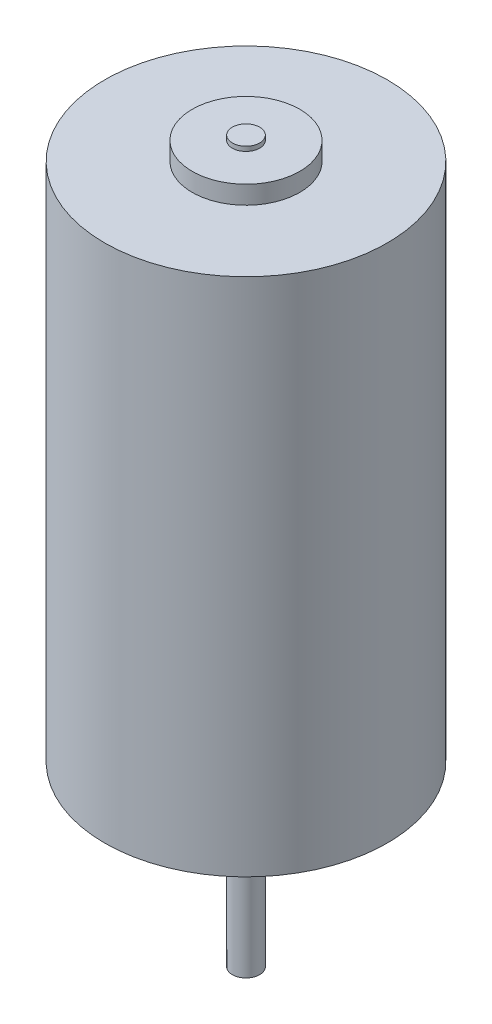
SolidWorks part; units mm, degrees
ref_plane "Plan de face" through (0, 0, 0) normal (0, 0, 1) x (1, 0, 0)
ref_plane "Plan de dessus" through (0, 0, 0) normal (0, 1, 0) x (1, 0, 0)
ref_plane "Plan de droite" through (0, 0, 0) normal (1, 0, 0) x (0, 0, -1)
sketch "Esquisse1" plane through (0, 0, 0) normal (0, 0, 1) x (1, 0, 0)
  line L0 (0, 0) -> (0, 72.0131) construction
  line L1 (0, -19.5) -> (0, 59.5)
  line L2 (0, 59.5) -> (1.5, 59.5)
  line L3 (1.5, 59.5) -> (1.5, 59)
  line L4 (1.5, 59) -> (5.9, 59)
  line L5 (5.9, 59) -> (5.9, 57)
  line L6 (5.9, 57) -> (15.5, 57)
  line L7 (15.5, 57) -> (15.5, 0)
  line L8 (15.5, 0) -> (5.9, 0)
  line L9 (1.5, -3) -> (1.5, -19.5)
  line L10 (1.5, -19.5) -> (0, -19.5)
  line L11 (1.5, -3) -> (5.9, -3)
  line L12 (5.9, -3) -> (5.9, 0)
  dimension "D1" = 31
  dimension "D2" = 3
  dimension "D3" = 19.5
  dimension "D4" = 11.8
  dimension "D5" = 3
  dimension "D6" = 2
  dimension "D7" = 57
  dimension "D8" = 79
revolve "Révolution1" add sketch "Esquisse1" angle 360 about L0
hole_wizard "Trou taraudé M3x0.51" positions "Esquisse2" profile "Esquisse3" tap size "M3x0.5" standard "Ansi Metric"
sketch "Esquisse2" plane through (0, 0, 0) normal (0, -1, 0) x (-1, 0, 0)
  circle A0 centre (0, 0) radius 11 construction
  point P0 (0, -11)
  point P2 (-11, 0)
  point P4 (0, 11)
  point P6 (11, 0)
  dimension "D1" = 22
sketch "Esquisse3" plane through (0, 0, 11) normal (1, 0, 0) x (0, 0, -1)
  line L0 (0, 0) -> (0, 9.2511)
  line L1 (0, 9.2511) -> (1.25, 8.5)
  line L2 (1.25, 8.5) -> (1.25, 0)
  line L5 (1.25, 0) -> (0, 0)
  line L10 (0, 9.2511) -> (-1.25, 8.5) construction
  line L11 (0, -6.35) -> (0, 107.95) construction
  dimension "Diamètre du trou pour taraudage" = 2.5
  dimension "Profondeur du trou pour taraudage" = 8.5
  dimension "Angle de pointe" = 118
cosmetic thread "Filetage de perçage1"
cosmetic thread "Filetage de perçage2"
cosmetic thread "Filetage de perçage3"
cosmetic thread "Filetage de perçage4"
